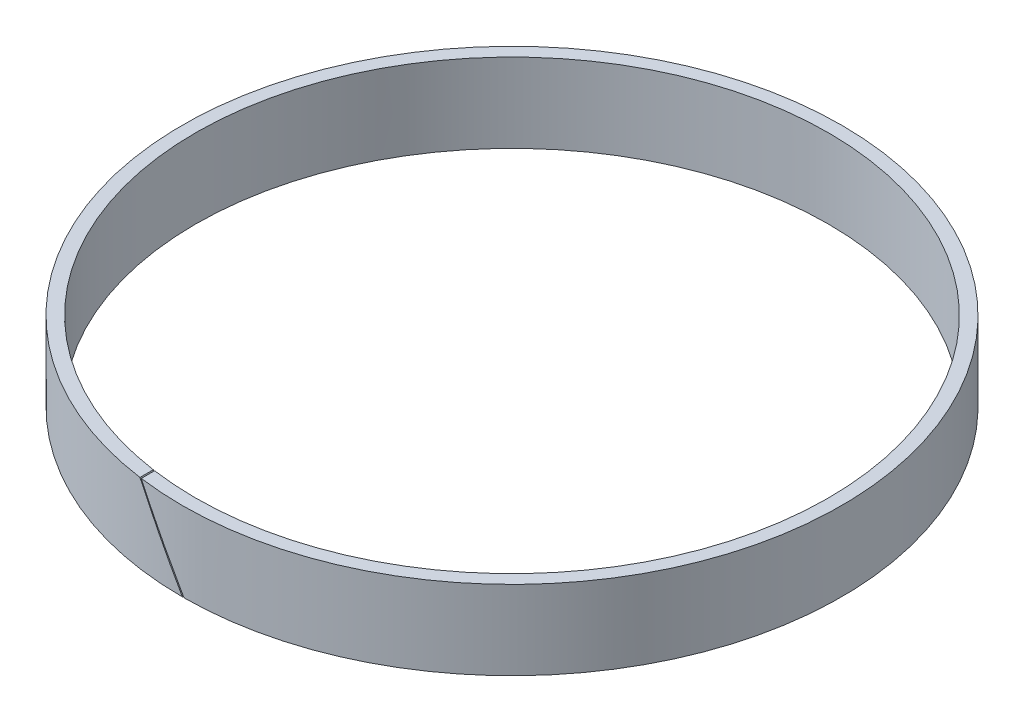
SolidWorks part; units mm, degrees
ref_plane "Front Plane" through (0, 0, 0) normal (0, 0, 1) x (1, 0, 0)
ref_plane "Top Plane" through (0, 0, 0) normal (0, 1, 0) x (1, 0, 0)
ref_plane "Right Plane" through (0, 0, 0) normal (1, 0, 0) x (0, 0, -1)
sketch "Sketch1" plane through (0, 0, 0) normal (0, 1, 0) x (1, 0, 0)
  circle A0 centre (0, 0) radius 25
  circle A1 centre (0, 0) radius 24
  dimension "D1" = 48
  dimension "D2" = 50
extrude "Boss-Extrude1" add sketch "Sketch1" along normal blind 6
sketch "Sketch2" plane through (0, 0, 0) normal (0, 0, 1) x (1, 0, 0)
  line L0 (0, 0) -> (0, 6) construction
  line L1 (25, 6) -> (-25, 6) construction
  line L2 (0, 0) -> (-3.4641, 6)
  line L4 (-3.4641, 6) -> (-3.3486, 6)
  line L5 (-3.3486, 6) -> (0.1155, 0)
  line L6 (-25, 0) -> (25, 0) construction
  line L7 (0.1155, 0) -> (0, 0)
  dimension "D1" = 30
  dimension "D2" = 0.1
extrude "Cut-Extrude1" cut sketch "Sketch2" along normal up to next
